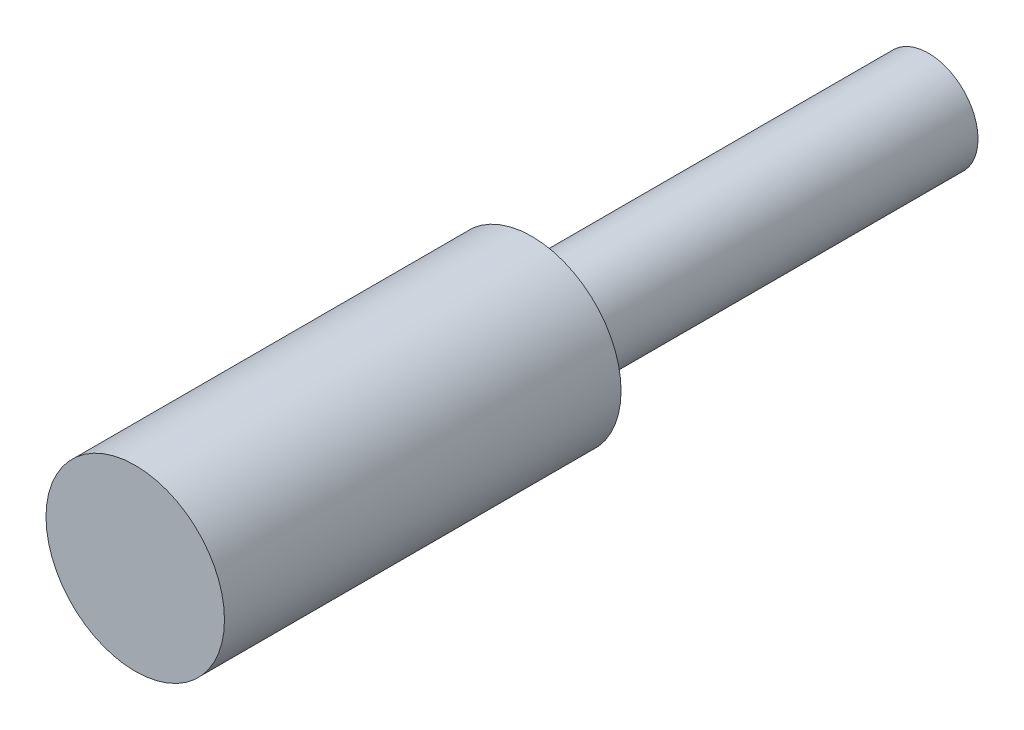
SolidWorks part; units mm, degrees
ref_plane "Front Plane" through (0, 0, 0) normal (0, 0, 1) x (1, 0, 0)
ref_plane "Top Plane" through (0, 0, 0) normal (0, 1, 0) x (1, 0, 0)
ref_plane "Right Plane" through (0, 0, 0) normal (1, 0, 0) x (0, 0, -1)
sketch "Sketch1" plane through (0, 0, 0) normal (0, 0, 1) x (1, 0, 0)
  circle A0 centre (0, 0) radius 2.5
  dimension "D1" = 5
extrude "Boss-Extrude1" add sketch "Sketch1" along normal blind 20
sketch "Sketch2" plane through (0, 0, 20) normal (0, 0, 1) x (1, 0, 0)
  circle A0 centre (0, 0) radius 4.5
  dimension "D1" = 9
extrude "Boss-Extrude2" add sketch "Sketch2" along normal blind 20
